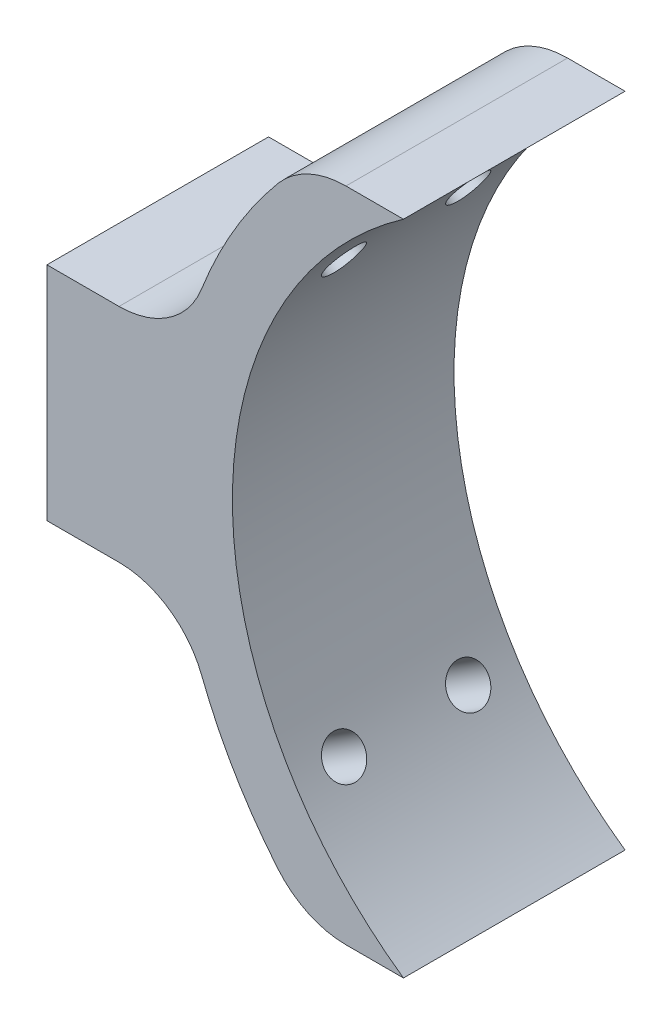
SolidWorks part; units mm, degrees
ref_plane "Front Plane" through (0, 0, 0) normal (0, 0, 1) x (1, 0, 0)
ref_plane "Top Plane" through (0, 0, 0) normal (0, 1, 0) x (1, 0, 0)
ref_plane "Right Plane" through (0, 0, 0) normal (1, 0, 0) x (0, 0, -1)
sketch "Sketch1" plane through (0, 0, 0) normal (0, 0, 1) x (1, 0, 0)
  line L0 (0, 0) -> (-66.175, 0) construction
  line L1 (-66.175, -12.5) -> (-66.175, 12.5)
  line L2 (0, 45.25) -> (0, 52.25) construction
  line L3 (-66.175, 12.5) -> (-50.7328, 12.5)
  line L4 (-66.175, -12.5) -> (-50.7328, -12.5)
  line L9 (-25.9543, -37.0666) -> (-36.8256, -37.0666)
  line L10 (-25.9543, 37.0666) -> (-36.8256, 37.0666)
  line L12 (0, 0) -> (-29.9694, -42.8007) construction
  circle A0 centre (0, 0) radius 45.25 construction
  circle A1 centre (0, 0) radius 52.25 construction
  arc A3 (-25.9543, 37.0666) -> (-25.9543, -37.0666) centre (0, 0) ccw
  arc A6 (-36.8256, -37.0666) -> (-50.7328, -12.5) centre (0, 0) cw
  arc A7 (-36.8256, 37.0666) -> (-50.7328, 12.5) centre (0, 0) ccw
  point P6 (-66.175, 0)
  point P10 (-62.175, -11)
  point P13 (-44.8058, -11)
  point P14 (-62.175, 11)
  point P15 (-44.8058, 11)
  dimension "D1" = 90.5
  dimension "D3" = 7
  dimension "D6" = 55
  dimension "D2" = 66.175
  dimension "D4" = 25
extrude "Boss-Extrude1" add sketch "Sketch1" along normal mid plane 25
sketch "Sketch2" plane through (0, 0, 0) normal (0, 0, 1) x (1, 0, 0)
  line L0 (0, 0) -> (-38.1635, 24.3128) construction
  line L1 (0, 0) -> (-45.25, 0) construction
  arc A0 (-25.9543, 37.0666) -> (-25.9543, -37.0666) centre (0, 0) ccw construction
  dimension "D1" = 32.5
ref_plane "Plane1" through (0, 0, 0) normal (-0.8434, 0.5373, 0) x (0, 0, 1)
sketch "Sketch3" plane through (0, 0, 0) normal (-0.8434, 0.5373, 0) x (0, 0, 1)
  line L0 (-7, 0) -> (7, 0) construction
  circle A1 centre (-7, 0) radius 2.25
  circle A2 centre (7, 0) radius 2.25
  point P3 (0, 0)
  point P7 (9.2497, 0)
  dimension "D1" = 4.5
  dimension "D2" = 14
extrude "Cut-Extrude1" cut sketch "Sketch3" along normal through all both and the other way through all
mirror "Mirror1" about plane through (0, 0, 0) normal (0, 1, 0) of "Cut-Extrude1"
sketch "Sketch5" plane through (-66.175, 0, 0) normal (-1, 0, 0) x (0, 0, 1)
  line L2 (-7, -7) -> (7, -7) construction
  line L4 (-7, -7) -> (-7, 7) construction
  line L5 (-7, 7) -> (7, 7) construction
  line L6 (7, -7) -> (7, 7) construction
  line L7 (0, 7) -> (0, -7) construction
  line L8 (-7, 0) -> (7, 0) construction
  circle A2 centre (-7, 7) radius 2.25
  circle A3 centre (7, 7) radius 2.25
  circle A4 centre (7, -7) radius 2.25
  circle A5 centre (-7, -7) radius 2.25
  point P0 (0, 0)
  point P13 (8.8032, 8.8032)
  point P14 (8.7402, 8.7402)
  dimension "D1" = 4.5
  dimension "D2" = 14
extrude "Cut-Extrude2" cut sketch "Sketch5" against normal blind 5 and the other way through all
fillet "Fillet4" radius 10 4 edges at (-36.8256, 37.0666, 0) (-36.8256, -37.0666, 0) (-50.7328, -12.5, 0) (-50.7328, 12.5, 0)
